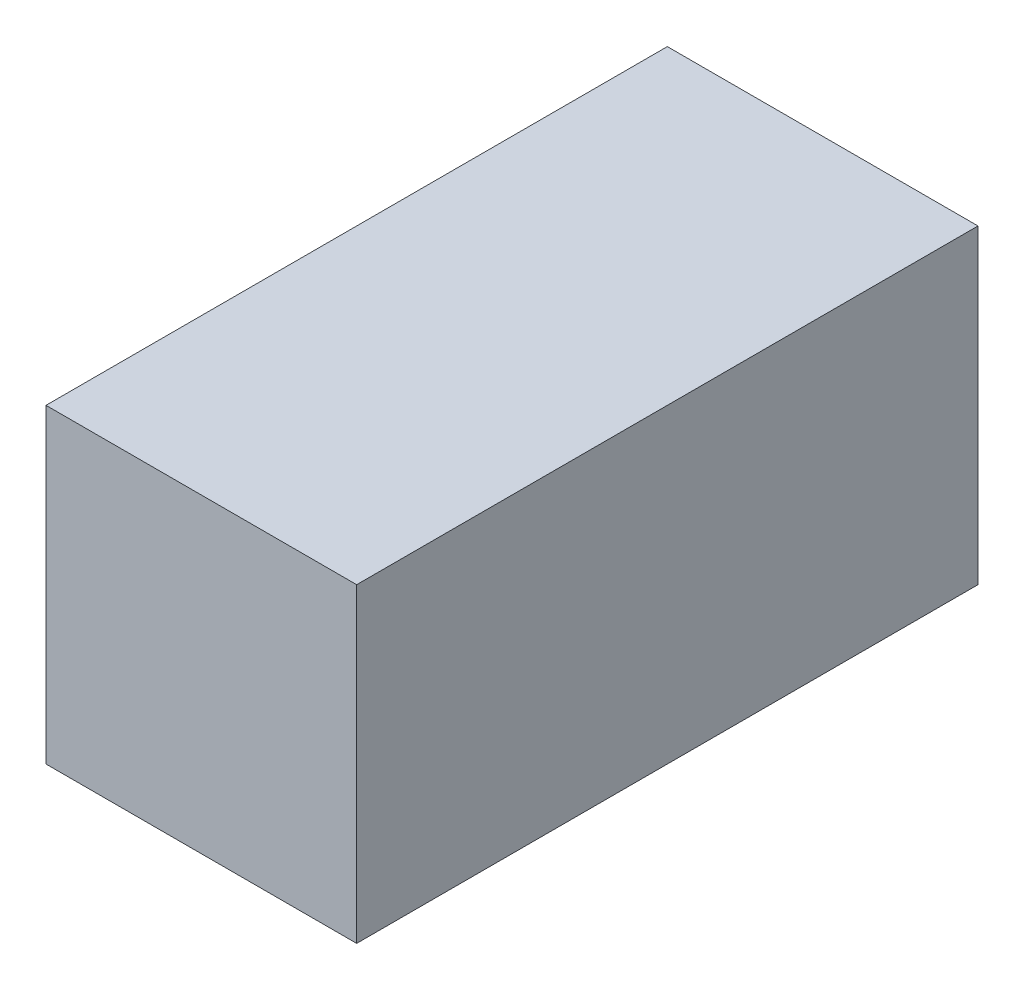
SolidWorks part; units mm, degrees
ref_plane "前视基准面" through (0, 0, 0) normal (0, 0, 1) x (1, 0, 0)
ref_plane "上视基准面" through (0, 0, 0) normal (0, 1, 0) x (1, 0, 0)
ref_plane "右视基准面" through (0, 0, 0) normal (1, 0, 0) x (0, 0, -1)
other "Configuration Table"
sketch "草图1" plane through (0, 0, 0) normal (0, 0, 1) x (1, 0, 0)
  line L1 (0, 0) -> (10, 0)
  line L2 (0, 0) -> (0, 10)
  line L3 (0, 10) -> (10, 10)
  line L4 (10, 0) -> (10, 10)
extrude "凸台-拉伸1" add sketch "草图1" along normal blind 20
